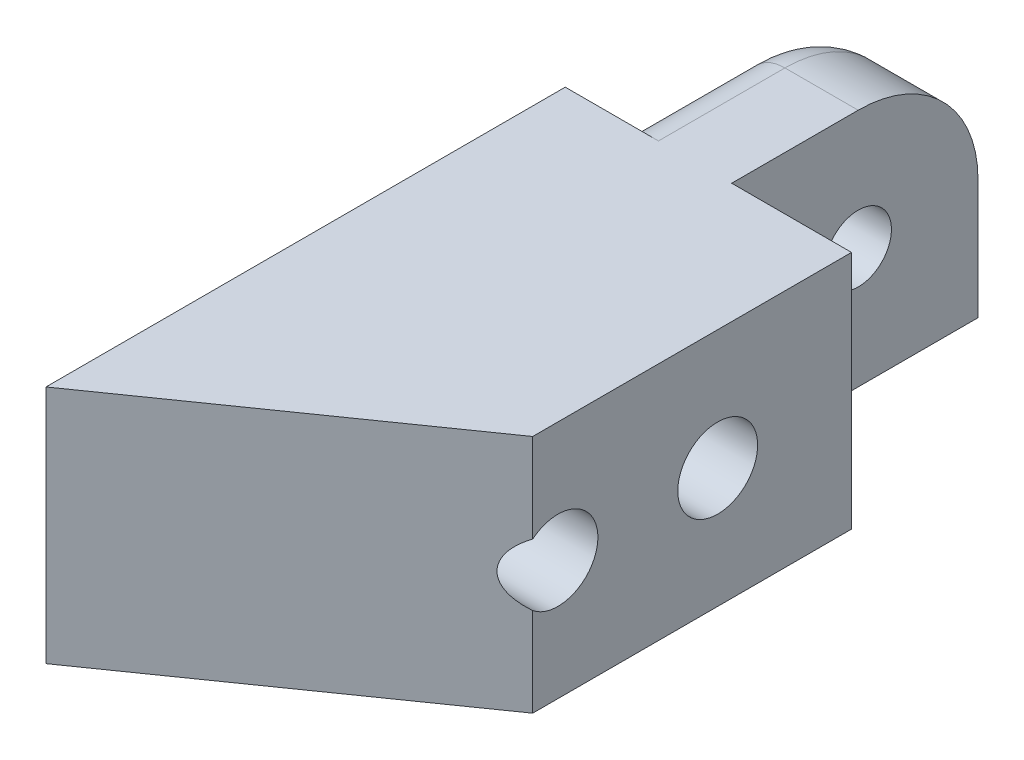
SolidWorks part; units mm, degrees
ref_plane "Front Plane" through (0, 0, 0) normal (0, 0, 1) x (1, 0, 0)
ref_plane "Top Plane" through (0, 0, 0) normal (0, 1, 0) x (1, 0, 0)
ref_plane "Right Plane" through (0, 0, 0) normal (1, 0, 0) x (0, 0, -1)
sketch "Sketch1" plane through (0, 0, 0) normal (0, 1, 0) x (1, 0, 0)
  line L0 (-8.25, 11.9728) -> (-8.25, -27.0272)
  line L1 (-8.25, -27.0272) -> (13.25, -11.9728)
  line L2 (13.25, -11.9728) -> (13.25, 11.9728)
  line L3 (13.25, 11.9728) -> (4.25, 11.9728)
  line L4 (4.25, 11.9728) -> (4.25, 30.4728)
  line L5 (4.25, 30.4728) -> (-4.25, 30.4728)
  line L6 (-4.25, 30.4728) -> (-4.25, 11.9728)
  line L7 (-4.25, 11.9728) -> (-8.25, 11.9728)
  line L8 (-8.25, 0) -> (13.25, 0) construction
  line L9 (0, 30.4728) -> (0, -21.2505) construction
  dimension "D1" = 9
  dimension "D2" = 4
  dimension "D3" = 8.5
  dimension "D4" = 18.5
  dimension "D5" = 39
  dimension "D6" = 55
extrude "Boss-Extrude1" add sketch "Sketch1" along normal blind 18
sketch "Sketch3" plane through (-8.25, 0, 0) normal (-1, 0, 0) x (0, 0, 1)
  line L0 (-21.4728, 18) -> (-21.4728, 0) construction
  line L1 (-30.4728, 9) -> (-30.4728, 18)
  line L2 (-30.4728, 18) -> (-21.4728, 18)
  line L3 (-30.4728, 18) -> (-11.9728, 18) construction
  line L5 (-30.4728, 18) -> (-30.4728, 0) construction
  line L6 (-30.4728, 9) -> (27.0272, 9) construction
  line L7 (27.0272, 18) -> (27.0272, 0) construction
  line L8 (-11.9728, 18) -> (-11.9728, 0) construction
  arc A0 (-21.4728, 18) -> (-30.4728, 9) centre (-21.4728, 9) ccw
  circle A1 centre (-21.4728, 9) radius 2.5
  circle A2 centre (-1.9228, 9) radius 3
  circle A3 centre (10.0772, 9) radius 3
  point P2 (-21.4728, 9)
  point P13 (-1.9228, 9)
  point P14 (10.0772, 9)
  dimension "D4" = 6
  dimension "D5" = 5
  dimension "D1" = 9
  dimension "D2" = 10.05
  dimension "D3" = 12
extrude "Cut-Extrude1" cut sketch "Sketch3" against normal through all
fillet "Fillet1" radius 3 3 edges at (-4.25, 18, -16.7228) (-4.25, 15.364, -27.8367) (-4.25, 4.5, -30.4728)
